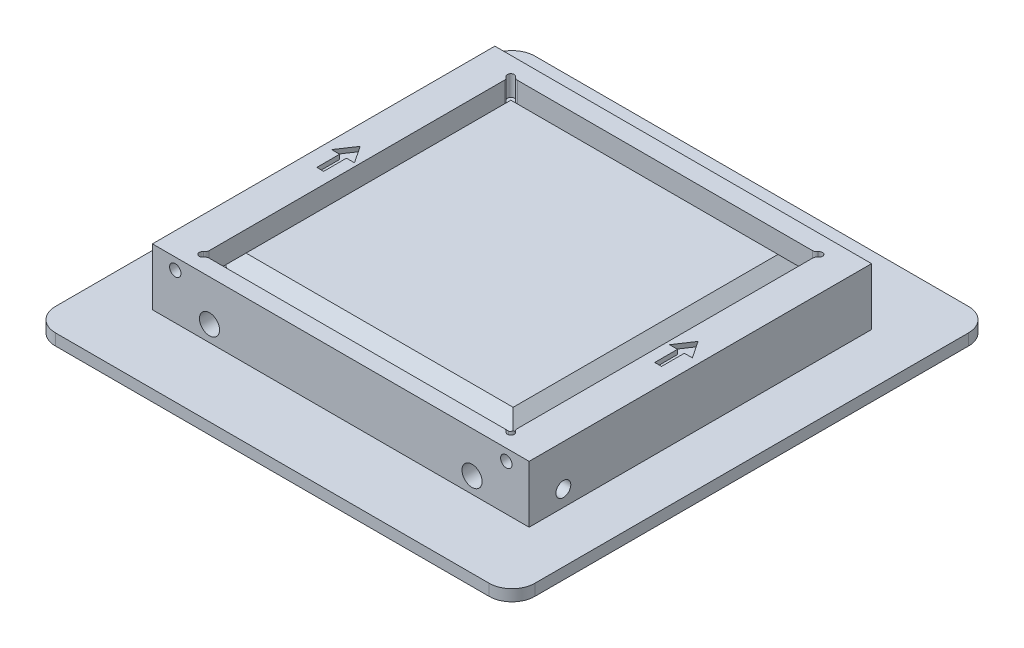
SolidWorks part; units mm, degrees
ref_plane "Front" through (0, 0, 0) normal (0, 0, 1) x (1, 0, 0)
ref_plane "Top" through (0, 0, 0) normal (0, 1, 0) x (1, 0, 0)
ref_plane "Right" through (0, 0, 0) normal (1, 0, 0) x (0, 0, -1)
sketch "Sketch1" plane through (0, 0, 0) normal (0, 1, 0) x (1, 0, 0)
  line L1 (-82.5, -75) -> (82.5, -75)
  line L2 (-82.5, -75) -> (-82.5, 75)
  line L3 (-82.5, 75) -> (82.5, 75)
  line L4 (82.5, -75) -> (82.5, 75)
  line L5 (-82.5, -75) -> (82.5, 75) construction
  line L6 (-82.5, 75) -> (82.5, -75) construction
  point P0 (0, 0)
  dimension "D1" = 165
  dimension "D2" = 150
extrude "Boss-Extrude1" add sketch "Sketch1" along normal blind 30
sketch "Sketch2" plane through (0, 30, 0) normal (0, 1, 0) x (1, 0, 0)
  line L0 (-63.5, 63) -> (-67.5, 63) construction
  line L1 (-63.5, -63) -> (63.5, -63)
  line L2 (-63.5, -63) -> (-63.5, 63)
  line L3 (-63.5, 63) -> (63.5, 63)
  line L4 (63.5, -63) -> (63.5, 63)
  line L5 (63.5, 63) -> (67.5, 63) construction
  line L6 (0, 63) -> (0, 67) construction
  line L7 (-67.5, -68) -> (67.5, -68)
  line L8 (-67.5, -68) -> (-67.5, 67)
  line L9 (-67.5, 67) -> (67.5, 67)
  line L10 (67.5, -68) -> (67.5, 67)
  point P0 (0, 0)
  point P6 (0, 0)
  point P13 (-63.5, 0)
  point P14 (0, -63)
  point P17 (0, 63)
  dimension "D1" = 127
  dimension "D2" = 4
  dimension "D5" = 126
extrude "Cut-Extrude1" cut sketch "Sketch2" against normal blind 9
sketch "Sketch3" plane through (0, 30, 0) normal (0, 1, 0) x (1, 0, 0)
  line L0 (75.5, -10) -> (72.5, -10)
  line L1 (72.5, -10) -> (72.5, 0)
  line L2 (72.5, 0) -> (69, 0)
  line L3 (69, 0) -> (74, 7.5)
  line L4 (74, 7.5) -> (79, 0)
  line L5 (79, 0) -> (75.5, 0)
  line L6 (75.5, 0) -> (75.5, -10)
  line L9 (82.5, -75) -> (82.5, 75) construction
  dimension "D1" = 3
  dimension "D2" = 10
  dimension "D3" = 10
  dimension "D4" = 7.5
  dimension "D5" = 7
extrude "Cut-Extrude2" cut sketch "Sketch3" against normal blind 2
mirror "Mirror1" about plane through (0, 0, 0) normal (1, 0, 0) of "Cut-Extrude2"
sketch "Sketch4" plane through (0, 0, 75) normal (0, 0, 1) x (1, 0, 0)
  line L0 (-72.5, 25) -> (72.5, 25) construction
  line L1 (-82.5, 30) -> (82.5, 30) construction
  circle A0 centre (72.5, 25) radius 2.5
  circle A1 centre (-72.5, 25) radius 2.5
  point P6 (0, 30)
  point P7 (0, 25)
  dimension "D2" = 5
  dimension "D1" = 145
  dimension "D3" = 5
extrude "Cut-Extrude3" cut sketch "Sketch4" against normal blind 11
sketch "Sketch5" plane through (0, 0, 0) normal (0, -1, 0) x (1, 0, 0)
  line L1 (-105, -105) -> (105, -105)
  line L2 (-105, -105) -> (-105, 105)
  line L3 (-105, 105) -> (105, 105)
  line L4 (105, -105) -> (105, 105)
  line L5 (-105, -105) -> (105, 105) construction
  line L6 (-105, 105) -> (105, -105) construction
  point P0 (0, 0)
  dimension "D1" = 210
extrude "Boss-Extrude2" add sketch "Sketch5" against normal blind 5
fillet "Fillet1" radius 10 4 edges at (-105, 2.5, -105) (105, 2.5, -105) (105, 2.5, 105) (-105, 2.5, 105)
sketch "Sketch6" plane through (0, 0, 75) normal (0, 0, 1) x (1, 0, 0)
  line L0 (-57.5, 12) -> (57.5, 12) construction
  line L1 (95, 0) -> (-95, 0) construction
  circle A0 centre (-57.5, 12) radius 4.4
  circle A1 centre (57.5, 12) radius 4.4
  point P4 (0, 12)
  dimension "D1" = 8.8
  dimension "D2" = 115
  dimension "D3" = 12
extrude "Cut-Extrude4" cut sketch "Sketch6" against normal through all
chamfer "Chamfer1" distance 5 angle 45 4 edges at (0, 30, 63) (-63.5, 30, 0) (0, 30, -63) (63.5, 30, 0)
sketch "Sketch7" plane through (0, 30, 0) normal (0, 1, 0) x (1, 0, 0)
  line L0 (-67.5, 65.5) -> (-67.5, 67)
  line L1 (-67.5, 67) -> (-66, 67)
  line L2 (66, 67) -> (67.5, 67)
  line L3 (67.5, 67) -> (67.5, 65.5)
  line L4 (66, -68) -> (67.5, -68)
  line L5 (67.5, -68) -> (67.5, -66.5)
  line L6 (-67.5, -66.5) -> (-67.5, -68)
  line L7 (-67.5, -68) -> (-66, -68)
  arc A0 (-66, 67) -> (-67.5, 65.5) centre (-67.5, 67) ccw
  arc A1 (67.5, 65.5) -> (66, 67) centre (67.5, 67) ccw
  arc A2 (66, -68) -> (67.5, -66.5) centre (67.5, -68) ccw
  arc A3 (-67.5, -66.5) -> (-66, -68) centre (-67.5, -68) ccw
  dimension "D1" = 3
extrude "Cut-Extrude5" cut sketch "Sketch7" against normal up to surface (9 mm away) up to face at (0, 21, 0)
fillet "Fillet2" radius 2 12 edges at (67.5, 25.5, -65.5) (66, 25.5, -67) (63.5, 23, -63) (66, 25.5, 68) (63.5, 23, 63) (67.5, 25.5, 66.5) (-63.5, 23, 63) (-66, 25.5, 68) (-67.5, 25.5, 66.5) (-67.5, 25.5, -65.5) (-63.5, 23, -63) (-66, 25.5, -67)
sketch "Sketch8" plane through (82.5, 0, 0) normal (1, 0, 0) x (0, 0, -1)
  line L0 (-75, 12) -> (-60, 12) construction
  line L1 (-75, 16.4) -> (-75, 7.6) construction
  circle A0 centre (-60, 12) radius 1.9
  dimension "D1" = 3.8
  dimension "D2" = 15
extrude "Cut-Extrude6" cut sketch "Sketch8" against normal blind 25
sketch "Sketch10" plane through (82.5, 0, 0) normal (1, 0, 0) x (0, 0, -1)
  circle A0 centre (-60, 12) radius 3.25
  dimension "D1" = 6.5
extrude "Cut-Extrude8" cut sketch "Sketch10" against normal blind 7.5
mirror "Mirror2" about plane through (0, 0, 0) normal (1, 0, 0) of "Cut-Extrude8", "Cut-Extrude6"
sketch "Sketch9" plane through (-82.5, 0, 0) normal (1, 0, 0) x (0, 0, -1)
  line L0 (0, 5) -> (0, 30) construction
  line L1 (-75, 5) -> (75, 5) construction
  line L2 (-75, 30) -> (75, 30) construction
  line L3 (-50, 17.5) -> (50, 17.5) construction
  circle A0 centre (-50, 17.5) radius 2.5
  circle A1 centre (50, 17.5) radius 2.5
  point P12 (0, 17.5)
  point P13 (0, 17.5)
  dimension "D1" = 5
  dimension "D2" = 100
extrude "Cut-Extrude7" cut sketch "Sketch9" along normal blind 10
